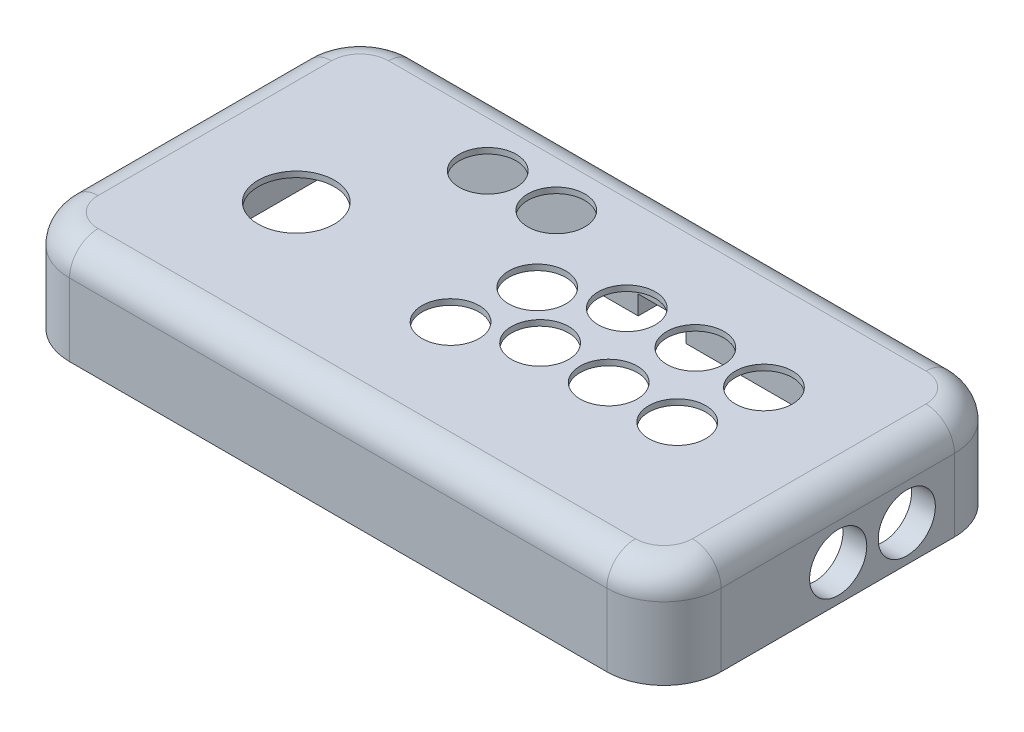
SolidWorks part; units mm, degrees
ref_plane "Front Plane" through (0, 0, 0) normal (0, 0, 1) x (1, 0, 0)
ref_plane "Top Plane" through (0, 0, 0) normal (0, 1, 0) x (1, 0, 0)
ref_plane "Right Plane" through (0, 0, 0) normal (1, 0, 0) x (0, 0, -1)
sketch "Sketch1" plane through (0, 0, 0) normal (0, 1, 0) x (1, 0, 0)
  line L1 (30, 0) -> (312, 0)
  line L2 (0, 30) -> (0, 152.5)
  line L3 (30, 182.5) -> (312, 182.5)
  line L4 (342, 30) -> (342, 152.5)
  circle A0 centre (165, 65) radius 15
  circle A1 centre (172, 103.5) radius 15
  circle A2 centre (198, 79) radius 15
  circle A3 centre (205, 117.5) radius 15
  circle A4 centre (234, 79) radius 15
  circle A5 centre (241, 117.5) radius 15
  circle A6 centre (270, 79) radius 15
  circle A7 centre (277, 117.5) radius 15
  circle A8 centre (70, 79) radius 20
  arc A9 (30, 182.5) -> (0, 152.5) centre (30, 152.5) ccw
  arc A10 (0, 30) -> (30, 0) centre (30, 30) ccw
  arc A11 (342, 30) -> (312, 0) centre (312, 30) cw
  arc A12 (342, 152.5) -> (312, 182.5) centre (312, 152.5) ccw
  circle A13 centre (106, 143.5) radius 15
  circle A14 centre (142, 143.5) radius 15
  point P26 (0, 182.5)
  point P29 (0, 0)
  point P32 (342, 0)
  point P35 (342, 182.5)
  dimension "D1" = 30
  dimension "D4" = 33
  dimension "D12" = 30
  dimension "D13" = 30
  dimension "D14" = 30
  dimension "D21" = 30
  dimension "D22" = 30
  dimension "D23" = 30
  dimension "D24" = 30
  dimension "D25" = 70
  dimension "D26" = 40
  dimension "D29" = 65
  dimension "D30" = 30
  dimension "D31" = 30
  dimension "D32" = 30
  dimension "D33" = 30
  dimension "D2" = 342
  dimension "D3" = 182.5
  dimension "D5" = 14
  dimension "D6" = 38.5
  dimension "D7" = 7
  dimension "D8" = 36
  dimension "D9" = 36
  dimension "D10" = 0
  dimension "D11" = 0
  dimension "D15" = 7
  dimension "D16" = 7
  dimension "D17" = 7
  dimension "D18" = 14
  dimension "D19" = 0
  dimension "D20" = 0
  dimension "D27" = 95
  dimension "D28" = 14
  dimension "D34" = 30
  dimension "D35" = 40
  dimension "D36" = 0
  dimension "D37" = 36
extrude "Boss-Extrude2" add sketch "Sketch1" along normal blind 3
sketch "Sketch2" plane through (0, 0, 0) normal (0, -1, 0) x (1, 0, 0)
  line L1 (30, 0) -> (312, 0)
  line L2 (0, -30) -> (0, -152.5)
  line L3 (30, -182.5) -> (312, -182.5)
  line L4 (342, -30) -> (342, -152.5)
  line L8 (12.5, -30) -> (12.5, -152.5)
  line L9 (30, -170) -> (312, -170)
  line L10 (329.5, -30) -> (329.5, -152.5)
  line L11 (30, -12.5) -> (312, -12.5)
  arc A0 (30, 0) -> (0, -30) centre (30, -30) ccw
  arc A1 (0, -152.5) -> (30, -182.5) centre (30, -152.5) ccw
  arc A2 (342, -152.5) -> (312, -182.5) centre (312, -152.5) cw
  arc A3 (342, -30) -> (312, 0) centre (312, -30) ccw
  arc A9 (12.5, -152.5) -> (30, -170) centre (30, -152.5) ccw
  arc A10 (329.5, -152.5) -> (312, -170) centre (312, -152.5) cw
  arc A11 (329.5, -30) -> (312, -12.5) centre (312, -30) ccw
  arc A12 (30, -12.5) -> (12.5, -30) centre (30, -30) ccw
  point P7 (0, 0)
  point P12 (342, -182.5)
  point P15 (342, 0)
  dimension "D3" = 30
  dimension "D4" = 30
  dimension "D5" = 30
  dimension "D1" = 342
  dimension "D2" = 182.5
  dimension "D7" = 12.5
extrude "Boss-Extrude4" add sketch "Sketch2" along normal blind 50
sketch "Sketch4" plane through (0, -50, 0) normal (0, -1, 0) x (1, 0, 0)
  line L0 (158.5, -170) -> (183.5, -170)
  line L3 (158.5, -170) -> (158.5, -182.5)
  line L4 (183.5, -170) -> (183.5, -182.5)
  line L5 (183.5, -182.5) -> (158.5, -182.5)
extrude "Cut-Extrude1" cut sketch "Sketch4" against normal blind 10
fillet "Fillet1" radius 15 8 edges at (8.7868, 3, -173.7132) (0, 3, -91.25) (8.7868, 3, -8.7868) (171, 3, -182.5) (333.2132, 3, -173.7132) (342, 3, -91.25) (171, 3, 0) (333.2132, 3, -8.7868)
sketch "Sketch6" plane through (342, 0, 0) normal (1, 0, 0) x (0, 0, -1)
  circle A0 centre (127.4669, -31) radius 15
  circle A1 centre (91.4669, -31) radius 15
  dimension "D1" = 30
  dimension "D2" = 30
  dimension "D3" = 36
  dimension "D4" = 0
extrude "Cut-Extrude2" cut sketch "Sketch6" against normal blind 40
